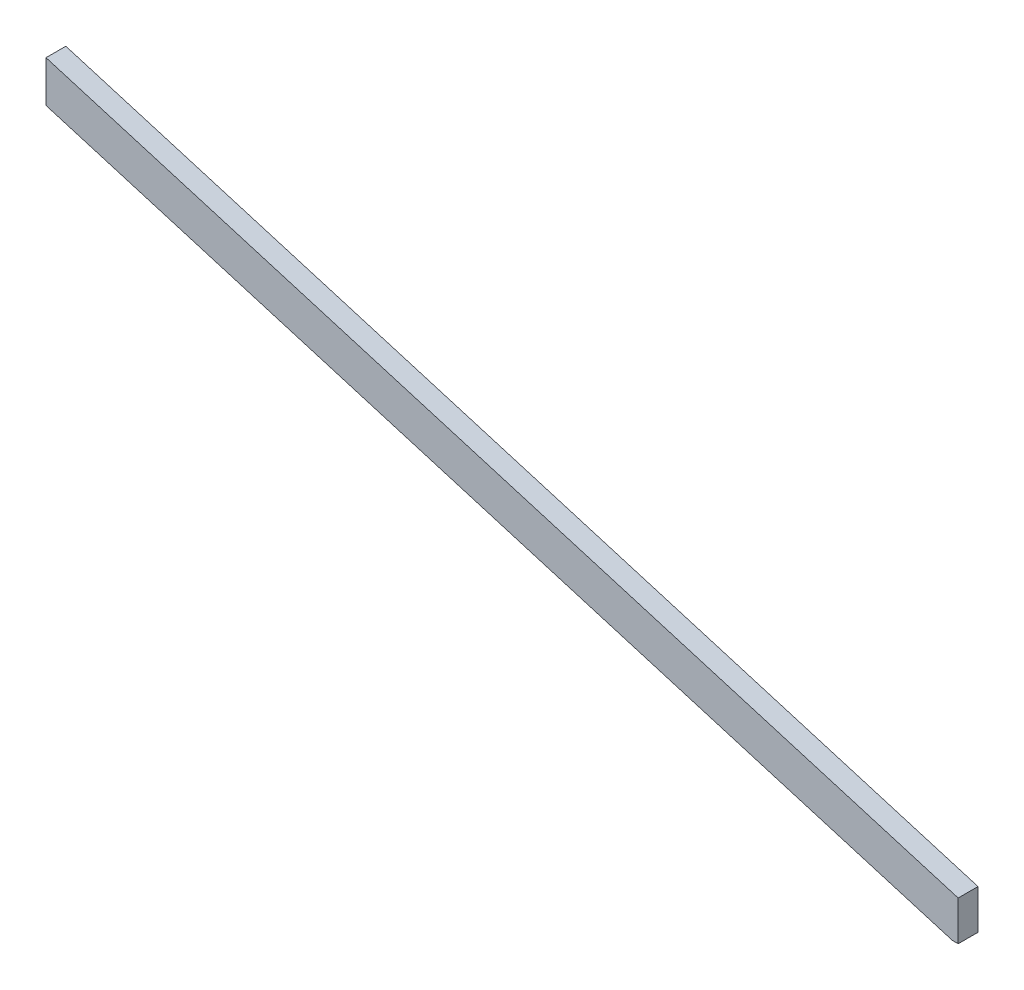
SolidWorks part; units mm, degrees
material "Pine"
ref_plane "Front Plane" through (0, 0, 0) normal (0, 0, 1) x (1, 0, 0)
ref_plane "Top Plane" through (0, 0, 0) normal (0, 1, 0) x (1, 0, 0)
ref_plane "Right Plane" through (0, 0, 0) normal (1, 0, 0) x (0, 0, -1)
sketch "Sketch3" plane through (0, 0, 50.8) normal (0, 0, 1) x (1, 0, 0)
  line L0 (-1384.025, 292.7405) -> (937.9681, -398.75)
  line L3 (-1384.025, 398.75) -> (-1384.025, 292.7405)
  line L4 (952.775, -297.15) -> (952.775, -398.75)
  line L8 (-1384.025, 398.75) -> (952.775, -297.15)
  line L9 (-1384.025, -1198.3) -> (-1384.025, 1240.1) construction
  line L10 (952.775, 398.75) -> (-1485.625, 398.75) construction
  line L11 (952.775, -398.75) -> (937.9681, -398.75)
  line L12 (952.775, -398.75) -> (-1485.625, -398.75) construction
  dimension "D1" = 101.6
extrude "Boss-Extrude2" add sketch "Sketch3" along normal blind 50.8
